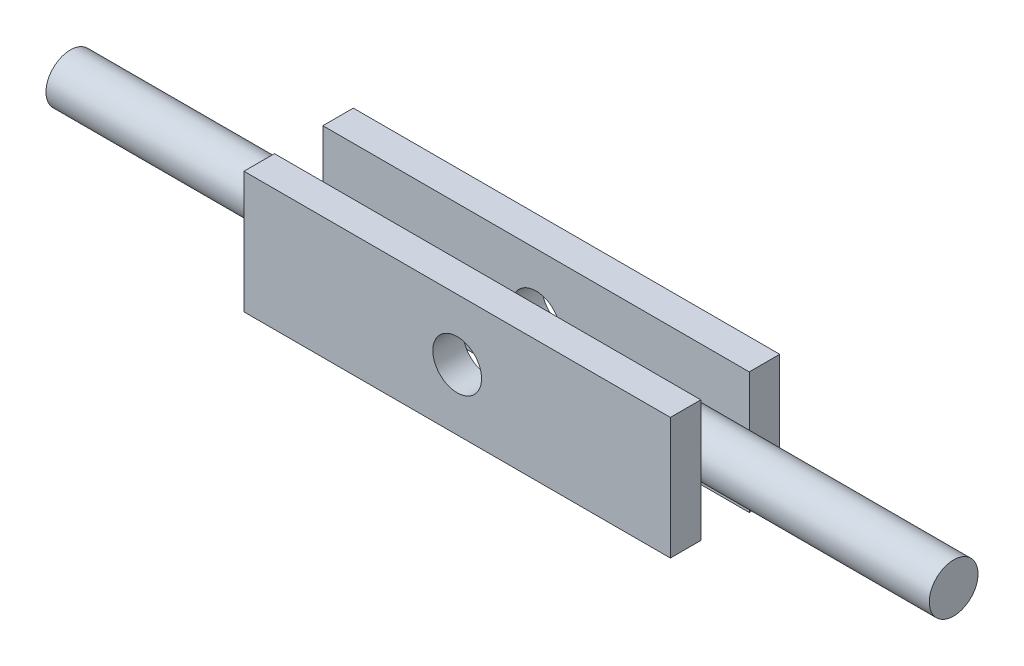
SolidWorks part; units mm, degrees
material "ASTM A36"
ref_plane "Front Plane" through (0, 0, 0) normal (0, 0, 1) x (1, 0, 0)
ref_plane "Top Plane" through (0, 0, 0) normal (0, 1, 0) x (1, 0, 0)
ref_plane "Right Plane" through (0, 0, 0) normal (1, 0, 0) x (0, 0, -1)
sketch "Sketch1" plane through (0, 0, 0) normal (0, 0, 1) x (1, 0, 0)
  line L1 (70, -20) -> (-70, -20)
  line L2 (70, -20) -> (70, 20)
  line L3 (70, 20) -> (-70, 20)
  line L4 (-70, -20) -> (-70, 20)
  line L5 (70, -20) -> (-70, 20) construction
  line L6 (70, 20) -> (-70, -20) construction
  point P0 (0, 0)
  dimension "D1" = 40
  dimension "D2" = 140
extrude "Boss-Extrude1" add sketch "Sketch1" along normal blind 10
sketch "Sketch4" plane through (0, 0, 10) normal (0, 0, 1) x (1, 0, 0)
  line L0 (-70, 20) -> (-70, -20) construction
  circle A0 centre (0, 0) radius 8
  dimension "D2" = 16
  dimension "D1" = 70
extrude "Cut-Extrude1" cut sketch "Sketch4" against normal blind 10
sketch "Sketch5" plane through (70, 0, 0) normal (1, 0, 0) x (0, 0, -1)
  line L0 (0, -20) -> (0, 20) construction
  circle A0 centre (8, 0) radius 8
  dimension "D1" = 16
  dimension "D2" = 8
extrude "Boss-Extrude2" add sketch "Sketch5" along normal blind 75 and the other way blind 20 separate body
pattern_linear "LPattern1" count 2 spacing 25.9 along (0, 0, -1) of "Boss-Extrude1"
sketch "Sketch6" plane through (0, 0, -25.9) normal (0, 0, -1) x (-1, 0, 0)
  line L0 (70, 20) -> (70, -20) construction
  circle A0 centre (0, 0) radius 8
  dimension "D1" = 70
  dimension "D2" = 16
extrude "Cut-Extrude2" cut sketch "Sketch6" against normal blind 100
sketch "Sketch7" plane through (-70, 0, 0) normal (-1, 0, 0) x (0, 0, 1)
  circle A0 centre (-8, 0) radius 8
extrude "Boss-Extrude3" add sketch "Sketch7" along normal blind 75 and the other way blind 20 separate body
